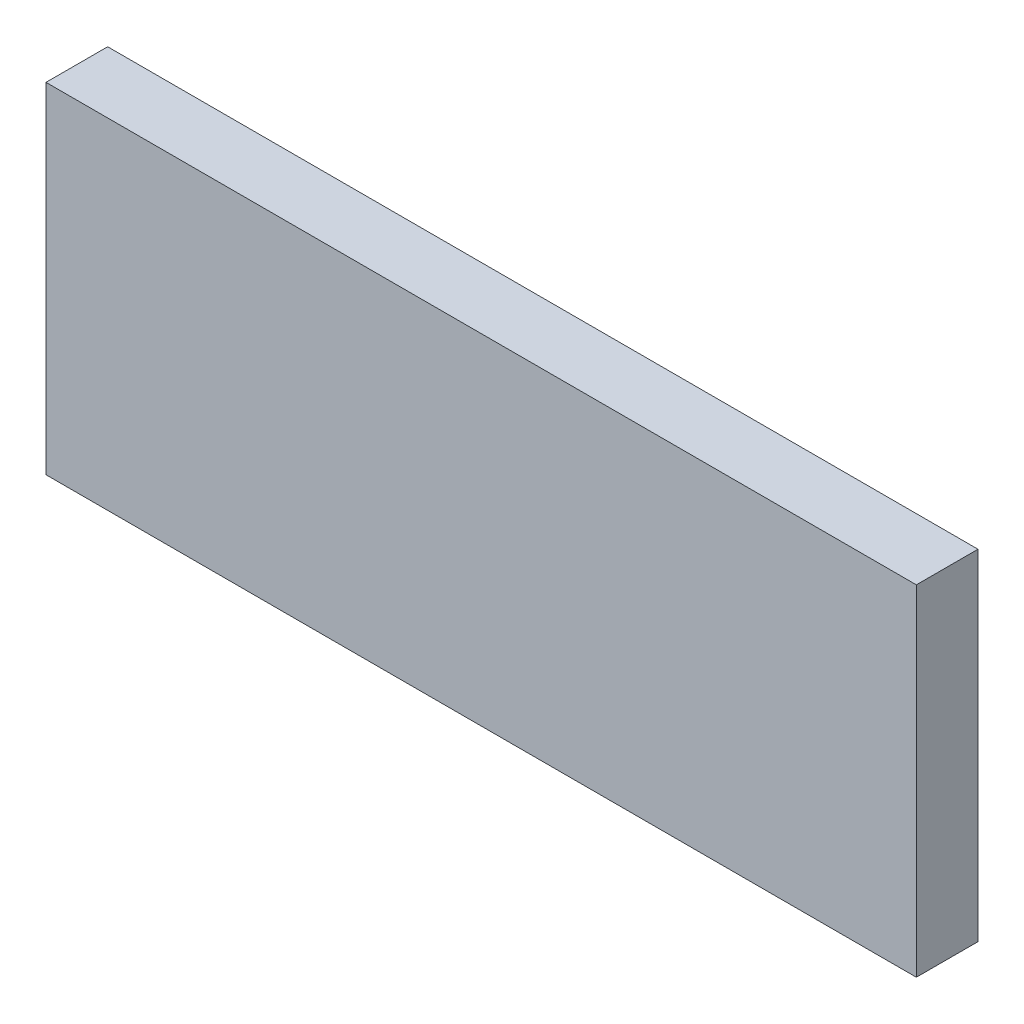
SolidWorks part; units mm, degrees
material "Acrylic (Medium-high impact)"
ref_plane "Front Plane" through (0, 0, 0) normal (0, 0, 1) x (1, 0, 0)
ref_plane "Top Plane" through (0, 0, 0) normal (0, 1, 0) x (1, 0, 0)
ref_plane "Right Plane" through (0, 0, 0) normal (1, 0, 0) x (0, 0, -1)
sketch "Sketch1" plane through (0, 0, 0) normal (0, 0, 1) x (1, 0, 0)
  line L1 (-44.815, -17.5) -> (44.815, -17.5)
  line L2 (-44.815, -17.5) -> (-44.815, 17.5)
  line L3 (-44.815, 17.5) -> (44.815, 17.5)
  line L4 (44.815, -17.5) -> (44.815, 17.5)
  line L5 (-44.815, -17.5) -> (44.815, 17.5) construction
  line L6 (-44.815, 17.5) -> (44.815, -17.5) construction
  point P0 (0, 0)
  dimension "D1" = 89.63
  dimension "D2" = 35
extrude "Boss-Extrude1" add sketch "Sketch1" along normal blind 6.35
